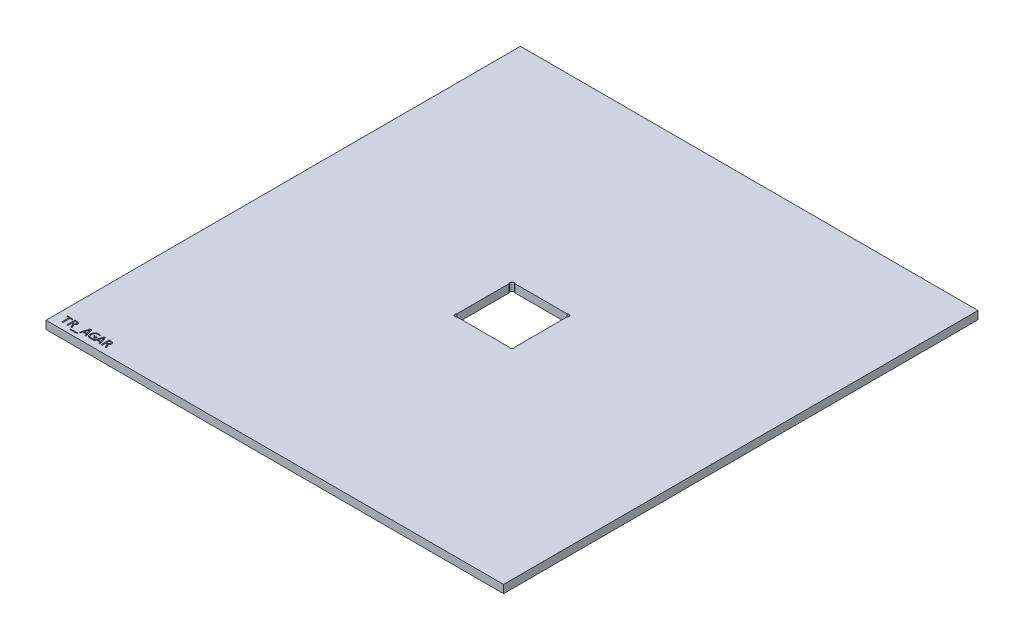
SolidWorks part; units mm, degrees
ref_plane "Front" through (0, 0, 0) normal (0, 0, 1) x (1, 0, 0)
ref_plane "Top" through (0, 0, 0) normal (0, 1, 0) x (1, 0, 0)
ref_plane "Right" through (0, 0, 0) normal (1, 0, 0) x (0, 0, -1)
sketch "Sketch1" plane through (0, 0, 0) normal (0, 1, 0) x (1, 0, 0)
  line L1 (-90.424, -93.7578) -> (90.424, -93.7578)
  line L2 (-90.424, -93.7578) -> (-90.424, 93.7578)
  line L3 (-90.424, 93.7578) -> (90.424, 93.7578)
  line L4 (90.424, -93.7578) -> (90.424, 93.7578)
  line L5 (-90.424, -93.7578) -> (90.424, 93.7578) construction
  line L6 (-90.424, 93.7578) -> (90.424, -93.7578) construction
  point P0 (0, 0)
  dimension "D1" = 180.848
  dimension "D2" = 187.5155
extrude "Boss-Extrude1" add sketch "Sketch1" along normal blind 3.175
sketch "Sketch2" plane through (0, 3.175, 0) normal (0, 1, 0) x (1, 0, 0)
  line L0 (-90.424, 93.7578) -> (90.424, -93.7578) construction
  line L2 (-11.43, -11.43) -> (11.43, -11.43)
  line L3 (-11.43, -11.43) -> (-11.43, 11.43)
  line L4 (-11.43, 11.43) -> (11.43, 11.43)
  line L5 (11.43, -11.43) -> (11.43, 11.43)
  line L6 (-11.43, -11.43) -> (11.43, 11.43) construction
  line L7 (-11.43, 11.43) -> (11.43, -11.43) construction
  point P4 (0, 0)
  dimension "D1" = 22.86
extrude "Cut-Extrude1" cut sketch "Sketch2" against normal blind 3.175
sketch "Sketch3" plane through (0, 3.175, 0) normal (0, 1, 0) x (1, 0, 0)
  line L0 (-11.43, 11.43) -> (-10.3075, 11.43) construction
  line L1 (11.43, 11.43) -> (-11.43, 11.43) construction
  line L2 (-11.43, 11.43) -> (-11.43, 10.3075) construction
  line L3 (11.43, 11.43) -> (11.43, 10.3075) construction
  line L4 (11.43, 11.43) -> (10.3075, 11.43) construction
  line L5 (11.43, -11.43) -> (10.3075, -11.43) construction
  line L6 (11.43, -11.43) -> (11.43, -10.3075) construction
  line L7 (-11.43, -11.43) -> (-11.43, -10.3075) construction
  line L8 (-11.43, -11.43) -> (-10.3075, -11.43) construction
  circle A0 centre (-10.8687, 10.8687) radius 0.7937
  circle A1 centre (10.8687, 10.8687) radius 0.7938
  circle A2 centre (10.8687, -10.8687) radius 0.7938
  circle A3 centre (-10.8687, -10.8687) radius 0.7938
  point P8 (0, 0)
  point P28 (0, 0)
  dimension "D1" = 1.5875
  dimension "D2" = 4
extrude "Cut-Extrude2" cut sketch "Sketch3" against normal through all
sketch "Sketch4" plane through (0, 3.175, 0) normal (0, 1, 0) x (1, 0, 0)
  line L0 (-87.884, -91.2177) -> (90.424, -91.2177) construction
  line L1 (-90.424, -93.7578) -> (-87.884, -93.7578) construction
  line L2 (-90.424, -93.7578) -> (-90.424, -91.2177) construction
  line L3 (-90.424, -91.2177) -> (-87.884, -91.2177) construction
  line L4 (-87.884, -93.7578) -> (-87.884, -91.2177) construction
  line L5 (90.424, -93.7578) -> (90.424, 93.7578) construction
  text T0 "TR_AGAR" font "Consolas" height 3.175
  dimension "D1" = 2.54
extrude "Cut-Extrude3" cut sketch "Sketch4" against normal blind 1.5875
